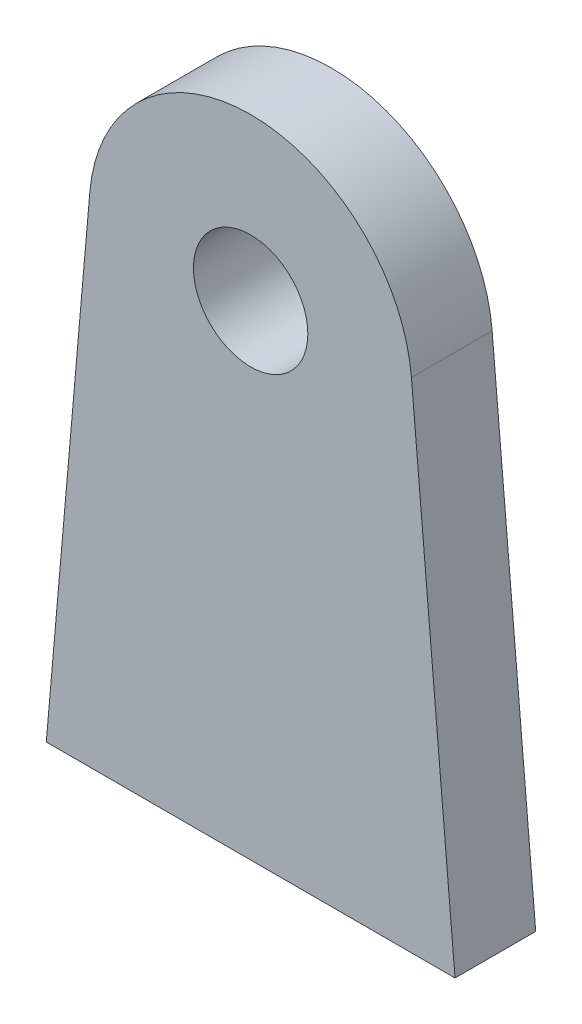
SolidWorks part; units mm, degrees
material "AISI 4130 Steel, annealed at 865C"
ref_plane "X-Y Datum" through (0, 0, 0) normal (0, 0, 1) x (1, 0, 0)
ref_plane "X-Z Datum" through (0, 0, 0) normal (0, 1, 0) x (1, 0, 0)
ref_plane "Y-Z Datum" through (0, 0, 0) normal (1, 0, 0) x (0, 0, -1)
sketch "Sketch1" plane through (0, 0, 0) normal (0, 0, 1) x (1, 0, 0)
  line L0 (0, 0) -> (16.0818, 0)
  line L1 (16.0818, 0) -> (14.3668, 19.6034)
  line L2 (0, 0) -> (1.7151, 19.6034)
  arc A0 (14.3668, 19.6034) -> (1.7151, 19.6034) centre (8.0409, 19.05) ccw
  point P8 (8.0409, 0)
  dimension "D1" = 6.35
  dimension "D2" = 10
  dimension "D3" = 19.05
extrude "Boss-Extrude1" add sketch "Sketch1" along normal blind 3.175
hole_wizard "M4 Clearance Hole1" positions "Sketch4" profile "Sketch3" hole size "M4" standard "ANSI Metric"
sketch "Sketch4" plane through (0, 0, 3.175) normal (0, 0, 1) x (1, 0, 0)
  point P0 (8.0409, 19.05)
sketch "Sketch3" plane through (8.0409, 19.05, 3.175) normal (1, 0, 0) x (0, -1, 0)
  line L0 (0, 0) -> (0, 17.3539)
  line L1 (0, 17.3539) -> (2.25, 16.002)
  line L2 (2.25, 16.002) -> (2.25, 0)
  line L5 (2.25, 0) -> (0, 0)
  line L10 (0, 17.3539) -> (-2.25, 16.002) construction
  line L11 (0, -6.35) -> (0, 107.95) construction
  dimension "Hole Dia." = 4.5
  dimension "Hole Depth" = 16.002
  dimension "Drill Angle" = 118
